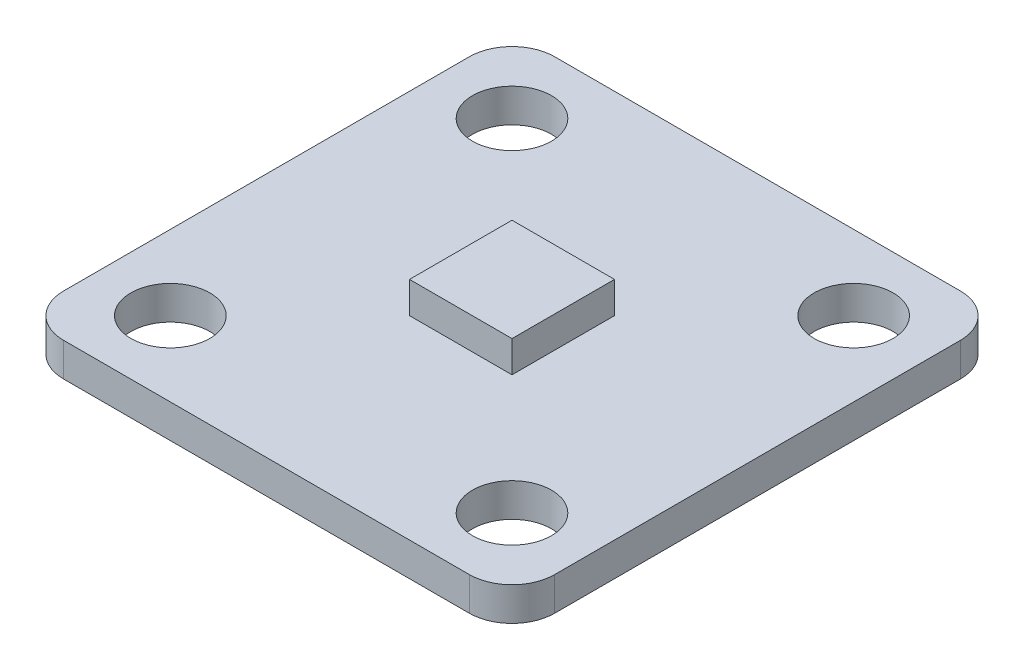
SolidWorks part; units mm, degrees
ref_plane "Front Plane" through (0, 0, 0) normal (0, 0, 1) x (1, 0, 0)
ref_plane "Top Plane" through (0, 0, 0) normal (0, 1, 0) x (1, 0, 0)
ref_plane "Right Plane" through (0, 0, 0) normal (1, 0, 0) x (0, 0, -1)
sketch "Sketch1" plane through (0, 0, 0) normal (0, 1, 0) x (1, 0, 0)
  line L1 (-9.5, -11.5) -> (9.5, -11.5)
  line L2 (-11.5, -9.5) -> (-11.5, 9.5)
  line L3 (-9.5, 11.5) -> (9.5, 11.5)
  line L4 (11.5, -9.5) -> (11.5, 9.5)
  line L5 (-11.5, -11.5) -> (11.5, 11.5) construction
  line L6 (-11.5, 11.5) -> (11.5, -11.5) construction
  line L7 (-8, -8) -> (8, -8) construction
  line L8 (-8, -8) -> (-8, 8) construction
  line L9 (-8, 8) -> (8, 8) construction
  line L10 (8, -8) -> (8, 8) construction
  line L11 (-8, -8) -> (8, 8) construction
  line L12 (-8, 8) -> (8, -8) construction
  line L13 (-2.4, -2.4) -> (2.4, -2.4)
  line L14 (-2.4, -2.4) -> (-2.4, 2.4)
  line L15 (-2.4, 2.4) -> (2.4, 2.4)
  line L16 (2.4, -2.4) -> (2.4, 2.4)
  line L17 (-2.4, -2.4) -> (2.4, 2.4) construction
  line L18 (-2.4, 2.4) -> (2.4, -2.4) construction
  arc A0 (-9.5, -11.5) -> (-11.5, -9.5) centre (-9.5, -9.5) cw
  arc A1 (9.5, -11.5) -> (11.5, -9.5) centre (9.5, -9.5) ccw
  arc A2 (9.5, 11.5) -> (11.5, 9.5) centre (9.5, 9.5) cw
  arc A3 (-11.5, 9.5) -> (-9.5, 11.5) centre (-9.5, 9.5) cw
  circle A4 centre (-8, 8) radius 1.85
  circle A5 centre (8, 8) radius 1.85
  circle A6 centre (8, -8) radius 1.85
  circle A7 centre (-8, -8) radius 1.85
  point P0 (0, 0)
  point P6 (0, 0)
  point P27 (0, 0)
  dimension "D5" = 2
  dimension "D6" = 3.7
  dimension "D1" = 23
  dimension "D2" = 23
  dimension "D3" = 16
  dimension "D4" = 16
  dimension "D7" = 4.8
  dimension "D8" = 4.8
extrude "Boss-Extrude1" add sketch "Sketch1" along normal blind 1.57 contours L13 L16 L15 L14 | A3 L2 A0 L1 A1 L4 A2 L3 A7 A6 A5 A4 L16 L13 L14 L15
sketch "Sketch2" plane through (0, 1.57, 0) normal (0, 1, 0) x (1, 0, 0)
  line L4 (-2.4, -2.4) -> (2.4, -2.4)
  line L5 (2.4, -2.4) -> (2.4, 2.4)
  line L6 (2.4, 2.4) -> (-2.4, 2.4)
  line L7 (-2.4, 2.4) -> (-2.4, -2.4)
  line L8 (-2.4, -2.4) -> (2.4, -2.4)
  line L9 (2.4, -2.4) -> (2.4, 2.4)
  line L10 (2.4, 2.4) -> (-2.4, 2.4)
  line L11 (-2.4, 2.4) -> (-2.4, -2.4)
  line L12 (-11.5, 9.5) -> (-11.5, -9.5)
  line L13 (-9.5, -11.5) -> (9.5, -11.5)
  line L14 (11.5, -9.5) -> (11.5, 9.5)
  line L15 (9.5, 11.5) -> (-9.5, 11.5)
  line L16 (-11.5, 9.5) -> (-11.5, -9.5)
  line L17 (-9.5, -11.5) -> (9.5, -11.5)
  line L18 (11.5, -9.5) -> (11.5, 9.5)
  line L19 (9.5, 11.5) -> (-9.5, 11.5)
  circle A1 centre (8, 8) radius 1.85
  circle A2 centre (8, 8) radius 1.85
  circle A3 centre (-8, -8) radius 1.85
  circle A4 centre (-8, -8) radius 1.85
  circle A5 centre (8, -8) radius 1.85
  circle A6 centre (8, -8) radius 1.85
  circle A7 centre (-8, 8) radius 1.85
  circle A8 centre (-8, 8) radius 1.85
  arc A12 (-11.5, -9.5) -> (-9.5, -11.5) centre (-9.5, -9.5) ccw
  arc A13 (9.5, -11.5) -> (11.5, -9.5) centre (9.5, -9.5) ccw
  arc A14 (11.5, 9.5) -> (9.5, 11.5) centre (9.5, 9.5) ccw
  arc A15 (-9.5, 11.5) -> (-11.5, 9.5) centre (-9.5, 9.5) ccw
  arc A16 (-11.5, -9.5) -> (-9.5, -11.5) centre (-9.5, -9.5) ccw
  arc A17 (9.5, -11.5) -> (11.5, -9.5) centre (9.5, -9.5) ccw
  arc A18 (11.5, 9.5) -> (9.5, 11.5) centre (9.5, 9.5) ccw
  arc A19 (-9.5, 11.5) -> (-11.5, 9.5) centre (-9.5, 9.5) ccw
  dimension "D1" = 0
  dimension "D2" = 0
  dimension "D3" = 0
  dimension "D4" = 0
  dimension "D5" = 0
  dimension "D6" = 0
extrude "Boss-Extrude2" add sketch "Sketch2" along normal blind 1.47 contours L10 L11 L8 L9
equation "\"a\"= 1"
equation "\"b\"= 1"
equation "\"c\"= 1"
equation "\"d\"= 1"
equation "\"e\"= 1"
equation "\"x\"= 1"
equation "\"y\"= 1"
equation "\"z\"= 1"
